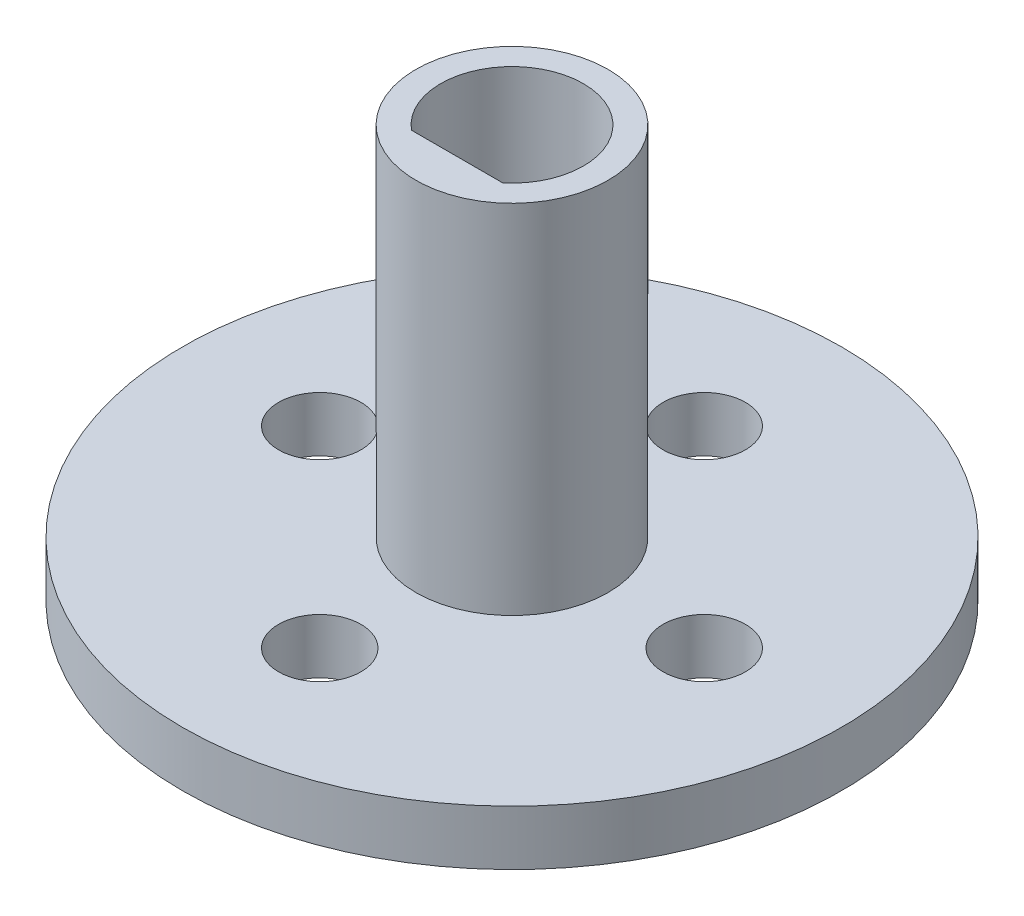
SolidWorks part; units mm, degrees
ref_plane "前视基准面" through (0, 0, 0) normal (0, 0, 1) x (1, 0, 0)
ref_plane "上视基准面" through (0, 0, 0) normal (0, 1, 0) x (1, 0, 0)
ref_plane "右视基准面" through (0, 0, 0) normal (1, 0, 0) x (0, 0, -1)
other "Configuration Table"
sketch "草图2" plane through (0, 0, 0) normal (0, 1, 0) x (1, 0, 0)
  line L0 (0, 0) -> (0, 7) construction
  circle A0 centre (0, 0) radius 12
  circle A1 centre (0, 7) radius 1.5
  circle A2 centre (7, 0) radius 1.5
  circle A3 centre (0, -7) radius 1.5
  circle A4 centre (-7, 0) radius 1.5
  point P14 (0, 0)
  dimension "D1" = 4
extrude "凸台-拉伸1" add sketch "草图2" along normal blind 2
sketch "草图3" plane through (0, 0, 0) normal (0, -1, 0) x (1, 0, 0)
  line L0 (-1.6613, 2) -> (1.6613, 2)
  circle A0 centre (0, 0) radius 3.5
  arc A1 (-1.6613, 2) -> (1.6613, 2) centre (0, 0) ccw
  point P6 (0, 2.6)
  dimension "D1" = 0.6
extrude "凸台-拉伸2" add sketch "草图3" against normal blind 15
sketch "草图4" plane through (0, 2, 0) normal (0, 1, 0) x (1, 0, 0)
  line L1 (-1.6613, -2) -> (1.6613, -2)
  line L2 (-1.6613, -2) -> (1.6613, -2)
  arc A1 (1.6613, -2) -> (-1.6613, -2) centre (0, 0) ccw
  arc A2 (1.6613, -2) -> (-1.6613, -2) centre (0, 0) ccw
  dimension "D1" = 0
extrude "切除-拉伸1" cut sketch "草图4" against normal through all
